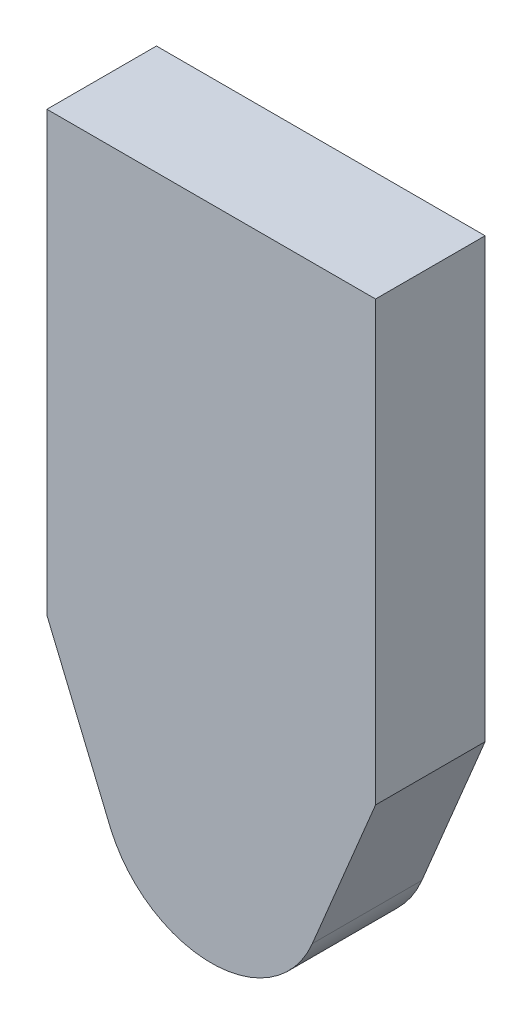
SolidWorks part; units mm, degrees
ref_plane "Front Plane" through (0, 0, 0) normal (0, 0, 1) x (1, 0, 0)
ref_plane "Top Plane" through (0, 0, 0) normal (0, 1, 0) x (1, 0, 0)
ref_plane "Right Plane" through (0, 0, 0) normal (1, 0, 0) x (0, 0, -1)
sketch "Sketch1" plane through (0, 0, 0) normal (0, 0, 1) x (1, 0, 0)
  line L0 (-9.525, 0) -> (9.525, 0)
  line L1 (-9.525, 0) -> (-5.8615, -8.7923)
  line L2 (5.8615, -8.7923) -> (9.525, 0)
  arc A0 (-5.8615, -8.7923) -> (5.8615, -8.7923) centre (0, -6.35) ccw
  point P4 (0, 0)
  dimension "D1" = 6.35
  dimension "D2" = 19.05
  dimension "D3" = 6.35
extrude "Boss-Extrude1" add sketch "Sketch1" along normal blind 6.35
sketch "Sketch2" plane through (0, 0, 6.35) normal (0, 0, 1) x (1, 0, 0)
  line L1 (-9.525, 0) -> (9.525, 0)
  line L2 (-9.525, 0) -> (-9.525, 25.4)
  line L3 (-9.525, 25.4) -> (9.525, 25.4)
  line L4 (9.525, 0) -> (9.525, 25.4)
  point P5 (9.525, 0)
  dimension "D1" = 25.4
extrude "Boss-Extrude2" add sketch "Sketch2" against normal blind 6.35
